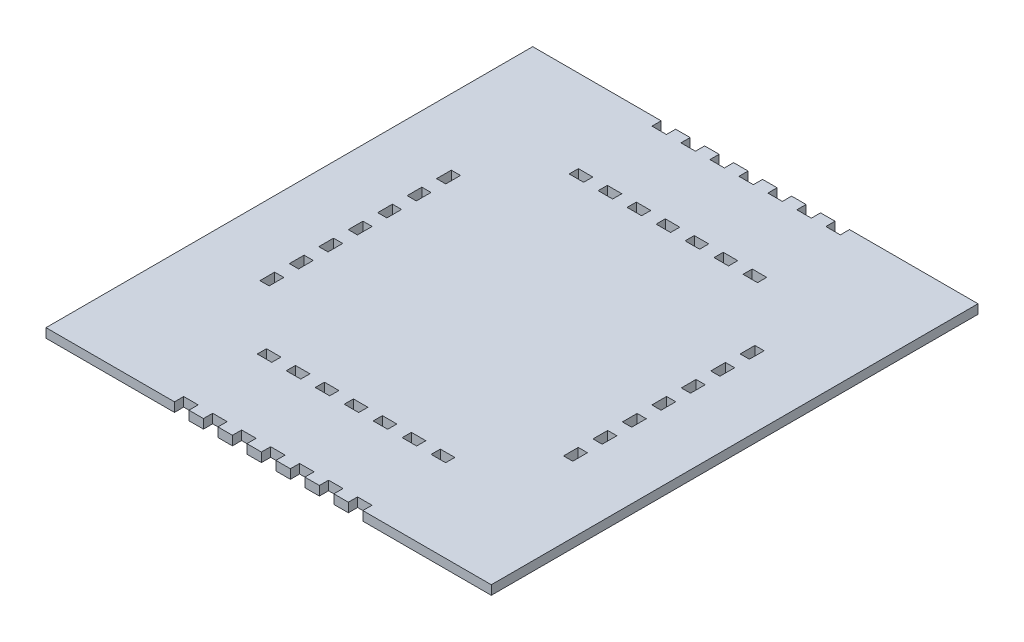
SolidWorks part; units mm, degrees
ref_plane "Front Plane" through (0, 0, 0) normal (0, 0, 1) x (1, 0, 0)
ref_plane "Top Plane" through (0, 0, 0) normal (0, 1, 0) x (1, 0, 0)
ref_plane "Right Plane" through (0, 0, 0) normal (1, 0, 0) x (0, 0, -1)
sketch "Sketch1" plane through (0, 0, 0) normal (0, 1, 0) x (1, 0, 0)
  line L0 (-34.4609, -83.0308) -> (-34.4609, -79.8558)
  line L1 (-34.4609, 84.9267) -> (-78.7959, 84.9267)
  line L2 (-78.7959, 84.9267) -> (-78.7959, -83.0308)
  line L3 (-78.7959, -83.0308) -> (-34.4609, -83.0308)
  line L4 (74.8741, 84.9267) -> (74.8741, -83.0308)
  line L5 (-34.4609, -79.8558) -> (-29.4609, -79.8558)
  line L6 (-29.4609, -79.8558) -> (-29.4609, -83.0308)
  line L7 (-19.4609, -79.8558) -> (-19.4609, -83.0308)
  line L8 (-24.4609, -79.8558) -> (-19.4609, -79.8558)
  line L9 (-24.4609, -83.0308) -> (-24.4609, -79.8558)
  line L10 (-9.4609, -79.8558) -> (-9.4609, -83.0308)
  line L11 (-14.4609, -79.8558) -> (-9.4609, -79.8558)
  line L12 (-14.4609, -83.0308) -> (-14.4609, -79.8558)
  line L13 (0.5391, -79.8558) -> (0.5391, -83.0308)
  line L14 (-4.4609, -79.8558) -> (0.5391, -79.8558)
  line L15 (-4.4609, -83.0308) -> (-4.4609, -79.8558)
  line L16 (10.5391, -79.8558) -> (10.5391, -83.0308)
  line L17 (5.5391, -79.8558) -> (10.5391, -79.8558)
  line L18 (5.5391, -83.0308) -> (5.5391, -79.8558)
  line L19 (20.5391, -79.8558) -> (20.5391, -83.0308)
  line L20 (15.5391, -79.8558) -> (20.5391, -79.8558)
  line L21 (15.5391, -83.0308) -> (15.5391, -79.8558)
  line L22 (30.5391, -79.8558) -> (30.5391, -83.0308)
  line L23 (25.5391, -79.8558) -> (30.5391, -79.8558)
  line L24 (25.5391, -83.0308) -> (25.5391, -79.8558)
  line L25 (-29.4609, -83.0308) -> (-24.4609, -83.0308)
  line L26 (-19.4609, -83.0308) -> (-14.4609, -83.0308)
  line L27 (-9.4609, -83.0308) -> (-4.4609, -83.0308)
  line L28 (0.5391, -83.0308) -> (5.5391, -83.0308)
  line L29 (10.5391, -83.0308) -> (15.5391, -83.0308)
  line L30 (20.5391, -83.0308) -> (25.5391, -83.0308)
  line L31 (30.5391, -83.0308) -> (74.8741, -83.0308)
  line L32 (-78.7959, 0.9479) -> (74.8741, 0.9479) construction
  line L33 (20.5391, 84.9267) -> (25.5391, 84.9267)
  line L34 (10.5391, 84.9267) -> (15.5391, 84.9267)
  line L35 (0.5391, 84.9267) -> (5.5391, 84.9267)
  line L36 (-9.4609, 84.9267) -> (-4.4609, 84.9267)
  line L37 (-19.4609, 84.9267) -> (-14.4609, 84.9267)
  line L38 (-29.4609, 84.9267) -> (-24.4609, 84.9267)
  line L39 (25.5391, 84.9267) -> (25.5391, 81.7517)
  line L40 (25.5391, 81.7517) -> (30.5391, 81.7517)
  line L41 (30.5391, 81.7517) -> (30.5391, 84.9267)
  line L42 (15.5391, 84.9267) -> (15.5391, 81.7517)
  line L43 (15.5391, 81.7517) -> (20.5391, 81.7517)
  line L44 (20.5391, 81.7517) -> (20.5391, 84.9267)
  line L45 (5.5391, 84.9267) -> (5.5391, 81.7517)
  line L46 (5.5391, 81.7517) -> (10.5391, 81.7517)
  line L47 (10.5391, 81.7517) -> (10.5391, 84.9267)
  line L48 (-4.4609, 84.9267) -> (-4.4609, 81.7517)
  line L49 (-4.4609, 81.7517) -> (0.5391, 81.7517)
  line L50 (0.5391, 81.7517) -> (0.5391, 84.9267)
  line L51 (-14.4609, 84.9267) -> (-14.4609, 81.7517)
  line L52 (-14.4609, 81.7517) -> (-9.4609, 81.7517)
  line L53 (-9.4609, 81.7517) -> (-9.4609, 84.9267)
  line L54 (-24.4609, 84.9267) -> (-24.4609, 81.7517)
  line L55 (-24.4609, 81.7517) -> (-19.4609, 81.7517)
  line L56 (-19.4609, 81.7517) -> (-19.4609, 84.9267)
  line L57 (-29.4609, 81.7517) -> (-29.4609, 84.9267)
  line L58 (-34.4609, 81.7517) -> (-29.4609, 81.7517)
  line L59 (-34.4609, 84.9267) -> (-34.4609, 81.7517)
  line L60 (30.5391, 84.9267) -> (74.8741, 84.9267)
  line L61 (-24.4609, 56.3517) -> (-19.4609, 56.3517)
  line L62 (-34.4609, 56.3517) -> (-29.4609, 56.3517)
  line L63 (-34.4609, 56.3517) -> (-34.4609, 53.1767)
  line L64 (-34.4609, 53.1767) -> (-29.4609, 53.1767)
  line L65 (-29.4609, 56.3517) -> (-29.4609, 53.1767)
  line L66 (-24.4609, 56.3517) -> (-24.4609, 53.1767)
  line L67 (-24.4609, 53.1767) -> (-19.4609, 53.1767)
  line L68 (-19.4609, 56.3517) -> (-19.4609, 53.1767)
  line L69 (-14.4609, 56.3517) -> (-9.4609, 56.3517)
  line L70 (-14.4609, 56.3517) -> (-14.4609, 53.1767)
  line L71 (-14.4609, 53.1767) -> (-9.4609, 53.1767)
  line L72 (-9.4609, 56.3517) -> (-9.4609, 53.1767)
  line L73 (-4.4609, 56.3517) -> (0.5391, 56.3517)
  line L74 (-4.4609, 56.3517) -> (-4.4609, 53.1767)
  line L75 (-4.4609, 53.1767) -> (0.5391, 53.1767)
  line L76 (0.5391, 56.3517) -> (0.5391, 53.1767)
  line L77 (5.5391, 56.3517) -> (10.5391, 56.3517)
  line L78 (5.5391, 56.3517) -> (5.5391, 53.1767)
  line L79 (5.5391, 53.1767) -> (10.5391, 53.1767)
  line L80 (10.5391, 56.3517) -> (10.5391, 53.1767)
  line L81 (15.5391, 56.3517) -> (20.5391, 56.3517)
  line L82 (15.5391, 56.3517) -> (15.5391, 53.1767)
  line L83 (15.5391, 53.1767) -> (20.5391, 53.1767)
  line L84 (20.5391, 56.3517) -> (20.5391, 53.1767)
  line L85 (25.5391, 56.3517) -> (30.5391, 56.3517)
  line L86 (25.5391, 56.3517) -> (25.5391, 53.1767)
  line L87 (25.5391, 53.1767) -> (30.5391, 53.1767)
  line L88 (30.5391, 56.3517) -> (30.5391, 53.1767)
  line L89 (-24.4609, -51.2808) -> (-19.4609, -51.2808)
  line L90 (-34.4609, -51.2808) -> (-29.4609, -51.2808)
  line L91 (-34.4609, -51.2808) -> (-34.4609, -54.4558)
  line L92 (-34.4609, -54.4558) -> (-29.4609, -54.4558)
  line L93 (-29.4609, -51.2808) -> (-29.4609, -54.4558)
  line L94 (-24.4609, -51.2808) -> (-24.4609, -54.4558)
  line L95 (-24.4609, -54.4558) -> (-19.4609, -54.4558)
  line L96 (-19.4609, -51.2808) -> (-19.4609, -54.4558)
  line L97 (-14.4609, -51.2808) -> (-9.4609, -51.2808)
  line L98 (-14.4609, -51.2808) -> (-14.4609, -54.4558)
  line L99 (-14.4609, -54.4558) -> (-9.4609, -54.4558)
  line L100 (-9.4609, -51.2808) -> (-9.4609, -54.4558)
  line L101 (-4.4609, -51.2808) -> (0.5391, -51.2808)
  line L102 (-4.4609, -51.2808) -> (-4.4609, -54.4558)
  line L103 (-4.4609, -54.4558) -> (0.5391, -54.4558)
  line L104 (0.5391, -51.2808) -> (0.5391, -54.4558)
  line L105 (5.5391, -51.2808) -> (10.5391, -51.2808)
  line L106 (5.5391, -51.2808) -> (5.5391, -54.4558)
  line L107 (5.5391, -54.4558) -> (10.5391, -54.4558)
  line L108 (10.5391, -51.2808) -> (10.5391, -54.4558)
  line L109 (15.5391, -51.2808) -> (20.5391, -51.2808)
  line L110 (15.5391, -51.2808) -> (15.5391, -54.4558)
  line L111 (15.5391, -54.4558) -> (20.5391, -54.4558)
  line L112 (20.5391, -51.2808) -> (20.5391, -54.4558)
  line L113 (25.5391, -51.2808) -> (30.5391, -51.2808)
  line L114 (25.5391, -51.2808) -> (25.5391, -54.4558)
  line L115 (25.5391, -54.4558) -> (30.5391, -54.4558)
  line L116 (30.5391, -51.2808) -> (30.5391, -54.4558)
  line L117 (-55.9359, 18.7279) -> (-52.7609, 18.7279)
  line L118 (-54.3484, -49.8521) -> (50.4266, -49.8521) construction
  line L119 (-54.3484, -32.0721) -> (-54.3484, 33.9679) construction
  line L120 (-54.3484, 51.7479) -> (50.4266, 51.7479) construction
  line L121 (50.4266, -49.8521) -> (50.4266, 51.7479) construction
  line L122 (-54.3484, -49.8521) -> (50.4266, 51.7479) construction
  line L123 (-54.3484, 51.7479) -> (50.4266, -49.8521) construction
  line L124 (-55.9359, 28.8879) -> (-52.7609, 28.8879)
  line L125 (-55.9359, 28.8879) -> (-55.9359, 33.9679)
  line L126 (-55.9359, 33.9679) -> (-52.7609, 33.9679)
  line L127 (-52.7609, 28.8879) -> (-52.7609, 33.9679)
  line L128 (-55.9359, 28.8879) -> (-52.7609, 33.9679) construction
  line L129 (-55.9359, 33.9679) -> (-52.7609, 28.8879) construction
  line L130 (-55.9359, 18.7279) -> (-55.9359, 23.8079)
  line L131 (-55.9359, 23.8079) -> (-52.7609, 23.8079)
  line L132 (-52.7609, 18.7279) -> (-52.7609, 23.8079)
  line L133 (-55.9359, 18.7279) -> (-52.7609, 23.8079) construction
  line L134 (-55.9359, 23.8079) -> (-52.7609, 18.7279) construction
  line L135 (-55.9359, 8.5679) -> (-52.7609, 8.5679)
  line L136 (-55.9359, 8.5679) -> (-55.9359, 13.6479)
  line L137 (-55.9359, 13.6479) -> (-52.7609, 13.6479)
  line L138 (-52.7609, 8.5679) -> (-52.7609, 13.6479)
  line L139 (-55.9359, 8.5679) -> (-52.7609, 13.6479) construction
  line L140 (-55.9359, 13.6479) -> (-52.7609, 8.5679) construction
  line L141 (-55.9359, -1.5921) -> (-52.7609, -1.5921)
  line L142 (-55.9359, -1.5921) -> (-55.9359, 3.4879)
  line L143 (-55.9359, 3.4879) -> (-52.7609, 3.4879)
  line L144 (-52.7609, -1.5921) -> (-52.7609, 3.4879)
  line L145 (-55.9359, -1.5921) -> (-52.7609, 3.4879) construction
  line L146 (-55.9359, 3.4879) -> (-52.7609, -1.5921) construction
  line L147 (-55.9359, -11.7521) -> (-52.7609, -11.7521)
  line L148 (-55.9359, -11.7521) -> (-55.9359, -6.6721)
  line L149 (-55.9359, -6.6721) -> (-52.7609, -6.6721)
  line L150 (-52.7609, -11.7521) -> (-52.7609, -6.6721)
  line L151 (-55.9359, -11.7521) -> (-52.7609, -6.6721) construction
  line L152 (-55.9359, -6.6721) -> (-52.7609, -11.7521) construction
  line L153 (-55.9359, -21.9121) -> (-52.7609, -21.9121)
  line L154 (-55.9359, -21.9121) -> (-55.9359, -16.8321)
  line L155 (-55.9359, -16.8321) -> (-52.7609, -16.8321)
  line L156 (-52.7609, -21.9121) -> (-52.7609, -16.8321)
  line L157 (-55.9359, -21.9121) -> (-52.7609, -16.8321) construction
  line L158 (-55.9359, -16.8321) -> (-52.7609, -21.9121) construction
  line L159 (-55.9359, -32.0721) -> (-52.7609, -32.0721)
  line L160 (-55.9359, -32.0721) -> (-55.9359, -26.9921)
  line L161 (-55.9359, -26.9921) -> (-52.7609, -26.9921)
  line L162 (-52.7609, -32.0721) -> (-52.7609, -26.9921)
  line L163 (-55.9359, -32.0721) -> (-52.7609, -26.9921) construction
  line L164 (-55.9359, -26.9921) -> (-52.7609, -32.0721) construction
  line L165 (-54.3484, -32.0721) -> (-54.3484, -49.8521) construction
  line L166 (-54.3484, 33.9679) -> (-54.3484, 51.7479) construction
  line L167 (-1.9609, 51.7479) -> (-1.9609, -49.8521) construction
  line L168 (52.0141, -26.9921) -> (48.8391, -32.0721) construction
  line L169 (52.0141, -32.0721) -> (48.8391, -26.9921) construction
  line L170 (52.0141, -16.8321) -> (48.8391, -21.9121) construction
  line L171 (52.0141, -21.9121) -> (48.8391, -16.8321) construction
  line L172 (52.0141, -6.6721) -> (48.8391, -11.7521) construction
  line L173 (52.0141, -11.7521) -> (48.8391, -6.6721) construction
  line L174 (52.0141, 3.4879) -> (48.8391, -1.5921) construction
  line L175 (52.0141, -1.5921) -> (48.8391, 3.4879) construction
  line L176 (52.0141, 13.6479) -> (48.8391, 8.5679) construction
  line L177 (52.0141, 8.5679) -> (48.8391, 13.6479) construction
  line L178 (52.0141, 23.8079) -> (48.8391, 18.7279) construction
  line L179 (52.0141, 18.7279) -> (48.8391, 23.8079) construction
  line L180 (52.0141, 33.9679) -> (48.8391, 28.8879) construction
  line L181 (52.0141, 28.8879) -> (48.8391, 33.9679) construction
  line L182 (50.4266, -32.0721) -> (50.4266, 33.9679) construction
  line L183 (48.8391, -32.0721) -> (48.8391, -26.9921)
  line L184 (52.0141, -26.9921) -> (48.8391, -26.9921)
  line L185 (52.0141, -32.0721) -> (52.0141, -26.9921)
  line L186 (52.0141, -32.0721) -> (48.8391, -32.0721)
  line L187 (48.8391, -21.9121) -> (48.8391, -16.8321)
  line L188 (52.0141, -16.8321) -> (48.8391, -16.8321)
  line L189 (52.0141, -21.9121) -> (52.0141, -16.8321)
  line L190 (52.0141, -21.9121) -> (48.8391, -21.9121)
  line L191 (48.8391, -11.7521) -> (48.8391, -6.6721)
  line L192 (52.0141, -6.6721) -> (48.8391, -6.6721)
  line L193 (52.0141, -11.7521) -> (52.0141, -6.6721)
  line L194 (52.0141, -11.7521) -> (48.8391, -11.7521)
  line L195 (48.8391, -1.5921) -> (48.8391, 3.4879)
  line L196 (52.0141, 3.4879) -> (48.8391, 3.4879)
  line L197 (52.0141, -1.5921) -> (52.0141, 3.4879)
  line L198 (52.0141, -1.5921) -> (48.8391, -1.5921)
  line L199 (48.8391, 8.5679) -> (48.8391, 13.6479)
  line L200 (52.0141, 13.6479) -> (48.8391, 13.6479)
  line L201 (52.0141, 8.5679) -> (52.0141, 13.6479)
  line L202 (52.0141, 8.5679) -> (48.8391, 8.5679)
  line L203 (48.8391, 18.7279) -> (48.8391, 23.8079)
  line L204 (52.0141, 23.8079) -> (48.8391, 23.8079)
  line L205 (52.0141, 18.7279) -> (52.0141, 23.8079)
  line L206 (48.8391, 28.8879) -> (48.8391, 33.9679)
  line L207 (52.0141, 33.9679) -> (48.8391, 33.9679)
  line L208 (52.0141, 28.8879) -> (52.0141, 33.9679)
  line L209 (52.0141, 28.8879) -> (48.8391, 28.8879)
  line L210 (52.0141, 18.7279) -> (48.8391, 18.7279)
  point P94 (-1.9609, 0.9479)
  point P123 (-54.3484, 31.4279)
  point P130 (-54.3484, 21.2679)
  point P135 (-54.3484, 11.1079)
  point P140 (-54.3484, 0.9479)
  point P145 (-54.3484, -9.2121)
  point P150 (-54.3484, -19.3721)
  point P155 (-54.3484, -29.5321)
  point P192 (50.4266, -29.5321)
  point P193 (50.4266, -19.3721)
  point P194 (50.4266, -9.2121)
  point P195 (50.4266, 0.9479)
  point P196 (50.4266, 11.1079)
  point P197 (50.4266, 21.2679)
  point P198 (50.4266, 31.4279)
  dimension "D1" = 153.67
  dimension "D2" = 167.9575
  dimension "D3" = 3.175
  dimension "D4" = 5
  dimension "D6" = 10
  dimension "D7" = 3.175
  dimension "D8" = 25.4
  dimension "D9" = 5
  dimension "D11" = 10
  dimension "D12" = 3.175
  dimension "D13" = 5
  dimension "D15" = 10
  dimension "D16" = 25.4
  dimension "D17" = 104.775
  dimension "D18" = 101.6
  dimension "D19" = 3.175
  dimension "D20" = 5.08
  dimension "D22" = 5.08
  dimension "D5" = 7
  dimension "D10" = 7
  dimension "D14" = 7
  dimension "D21" = 7
extrude "Boss-Extrude1" add sketch "Sketch1" along normal blind 3.175
